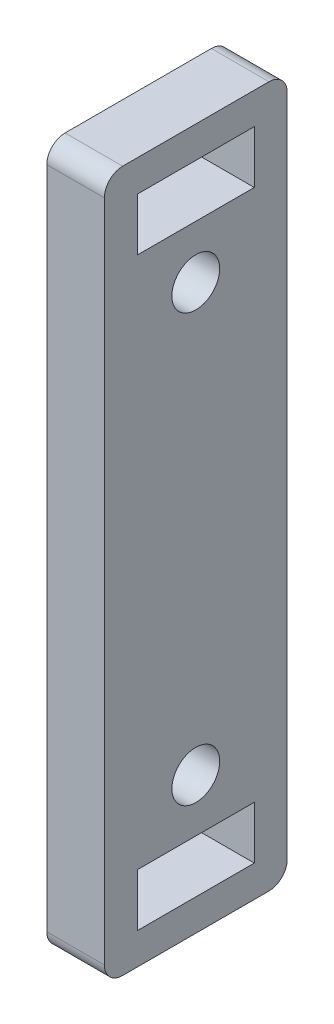
SolidWorks part; units mm, degrees
ref_plane "Front Plane" through (0, 0, 0) normal (0, 0, 1) x (1, 0, 0)
ref_plane "Top Plane" through (0, 0, 0) normal (0, 1, 0) x (1, 0, 0)
ref_plane "Right Plane" through (0, 0, 0) normal (1, 0, 0) x (0, 0, -1)
sketch "Sketch1" plane through (0, 0, 0) normal (1, 0, 0) x (0, 0, -1)
  line L1 (3.048, 16.613) -> (-3.048, 16.613) construction
  line L2 (3.048, 16.613) -> (3.048, 13.867) construction
  line L3 (3.048, 13.867) -> (-3.048, 13.867) construction
  line L4 (-3.048, 16.613) -> (-3.048, 13.867) construction
  line L5 (3.048, 16.613) -> (-3.048, 13.867) construction
  line L6 (3.048, 13.867) -> (-3.048, 16.613) construction
  line L11 (6.35, -19.05) -> (-6.35, -19.05) construction
  line L12 (6.35, -19.05) -> (6.35, 19.05) construction
  line L13 (6.35, 19.05) -> (-6.35, 19.05) construction
  line L14 (-6.35, -19.05) -> (-6.35, 19.05) construction
  line L15 (6.35, -19.05) -> (-6.35, 19.05) construction
  line L16 (6.35, 19.05) -> (-6.35, -19.05) construction
  line L17 (4.7625, -18.2562) -> (-4.7625, -18.2562)
  line L18 (4.7625, -18.2562) -> (4.7625, 18.2562)
  line L19 (4.7625, 18.2562) -> (-4.7625, 18.2562)
  line L20 (-4.7625, -18.2562) -> (-4.7625, 18.2562)
  line L21 (4.7625, -18.2562) -> (-4.7625, 18.2562) construction
  line L22 (4.7625, 18.2562) -> (-4.7625, -18.2562) construction
  point P0 (0, 15.24)
  point P5 (0, 0)
  point P12 (0, 0)
  dimension "D1" = 6.096
  dimension "D2" = 2.746
  dimension "D3" = 12.7
  dimension "D4" = 38.1
  dimension "D5" = 3.81
  dimension "D6" = 36.5125
  dimension "D7" = 9.525
extrude "Boss-Extrude1" add sketch "Sketch1" along normal mid plane 3
fillet "Fillet1" radius 0.9525 4 edges at (0, 18.2562, -4.7625) (0, -18.2562, -4.7625) (0, -18.2562, 4.7625) (0, 18.2562, 4.7625)
sketch "Sketch2" plane through (1.5, 0, 0) normal (1, 0, 0) x (0, 0, -1)
  line L1 (3.048, 16.613) -> (-3.048, 16.613)
  line L2 (3.048, 16.613) -> (3.048, 13.867)
  line L3 (3.048, 13.867) -> (-3.048, 13.867)
  line L4 (-3.048, 16.613) -> (-3.048, 13.867)
  line L5 (3.048, 16.613) -> (-3.048, 13.867) construction
  line L6 (3.048, 13.867) -> (-3.048, 16.613) construction
  line L7 (6.35, -19.05) -> (-6.35, -19.05) construction
  line L8 (6.35, -19.05) -> (6.35, 19.05) construction
  line L9 (6.35, 19.05) -> (-6.35, 19.05) construction
  line L10 (-6.35, -19.05) -> (-6.35, 19.05) construction
  line L11 (6.35, -19.05) -> (-6.35, 19.05) construction
  line L12 (6.35, 19.05) -> (-6.35, -19.05) construction
  circle A0 centre (0, 11.1125) radius 1.246
  point P0 (0, 15.24)
  point P5 (0, 0)
  point P11 (0, 8.9366)
  point P14 (0.109, 11.3196)
  point P15 (0, 0)
  dimension "D6" = 2.492
  dimension "D1" = 12.7
  dimension "D2" = 38.1
  dimension "D3" = 3.81
  dimension "D4" = 6.096
  dimension "D5" = 2.746
  dimension "D7" = 11.1125
extrude "Cut-Extrude1" cut sketch "Sketch2" against normal through all
mirror "Mirror1" about plane through (0, 0, 0) normal (0, 1, 0) of "Cut-Extrude1"
